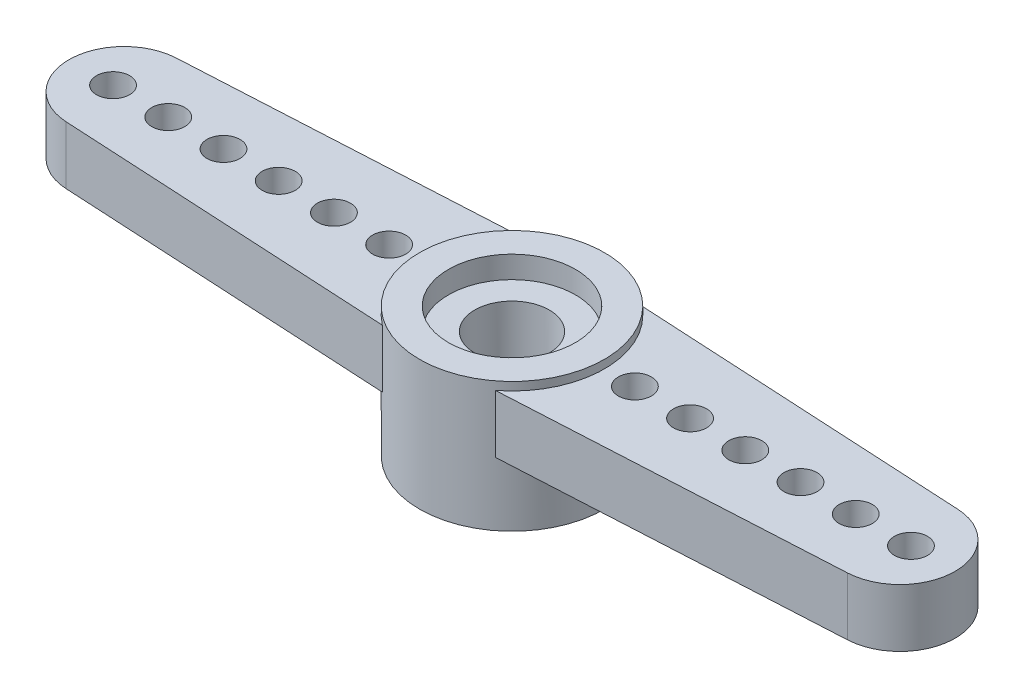
SolidWorks part; units mm, degrees
material "PVC Rígido"
ref_plane "Plano frontal" through (0, 0, 0) normal (0, 0, 1) x (1, 0, 0)
ref_plane "Plano superior" through (0, 0, 0) normal (0, 1, 0) x (1, 0, 0)
ref_plane "Plano direito" through (0, 0, 0) normal (1, 0, 0) x (0, 0, -1)
sketch "Esboço1" plane through (0, 0, 0) normal (0, 1, 0) x (1, 0, 0)
  line L0 (0, 0) -> (-14.05, 0) construction
  line L1 (-14.1577, 1.9971) -> (-2.0494, 2.65)
  line L2 (-2.0494, -2.65) -> (-14.1577, -1.9971)
  arc A0 (-2.0494, -2.65) -> (-2.0494, 2.65) centre (0, 0) ccw
  arc A1 (-14.1577, 1.9971) -> (-14.1577, -1.9971) centre (-14.05, 0) ccw
  point P5 (-16.05, 0)
  dimension "D1" = 6.7
  dimension "D2" = 4
  dimension "D3" = 16.05
  dimension "D4" = 5.3
extrude "Ressalto-extrusão1" add sketch "Esboço1" against normal blind 2.1
sketch "Esboço2" plane through (0, -2.1, 0) normal (0, -1, 0) x (1, 0, 0)
  arc A0 (-2.0494, -2.65) -> (-2.0494, 2.65) centre (0, 0) ccw construction
  circle A1 centre (0, 0) radius 3.35
extrude "Ressalto-extrusão2" add sketch "Esboço2" along normal offset from surface (2.3 mm away) 4.4 up to face at (-7.2268, 0, 0)
hole_wizard "Furo4" positions "Esboço9" profile "Esboço10" legacy end condition through all
sketch "Esboço9" plane through (0, 0, 0) normal (0, 1, 0) x (1, 0, 0)
  line L1 (-14.45, 0) -> (0, 0) construction
  arc A2 (-14.1577, 1.9971) -> (-14.1577, -1.9971) centre (-14.05, 0) ccw construction
  point P0 (-14.45, 0)
  point P19 (-16.05, 0)
  dimension "D1" = 1.6
sketch "Esboço10" plane through (-14.45, 0, 0) normal (1, 0, 0) x (0, 0, 1)
  line L0 (0, 0) -> (0, 4.4)
  line L1 (0, 4.4) -> (0.6, 4.4)
  line L2 (0.6, 4.4) -> (0.6, 0)
  line L3 (0.6, 0) -> (0, 0)
  line L4 (0, 110) -> (0, -10) construction
  dimension "Diameter" = 1.2
  dimension "Depth" = 4.4
pattern_linear "Padrão linear1" count 6 spacing 2 along (1, 0, 0) of "Furo4"
pattern_circular "PadrãoCircular2" count 2 over 360 about axis through (0, 0, 0) along (0, 1, 0) of "Ressalto-extrusão1", "Furo4", "Padrão linear1"
hole_wizard "Furo1" positions "Esboço3" profile "Esboço4" legacy
sketch "Esboço3" plane through (0, -4.4, 0) normal (0, -1, 0) x (-1, 0, 0)
  point P0 (0, 0)
sketch "Esboço4" plane through (0, -4.4, 0) normal (1, 0, 0) x (0, 0, -1)
  line L0 (0, 0) -> (0, 2)
  line L1 (0, 2) -> (2.475, 2)
  line L2 (2.475, 2) -> (2.475, 0)
  line L3 (2.475, 0) -> (0, 0)
  line L4 (0, 110) -> (0, -10) construction
  dimension "Diameter" = 4.95
  dimension "Depth" = 2
hole_wizard "Furo2" positions "Esboço5" profile "Esboço6" legacy
sketch "Esboço5" plane through (0, 0, 0) normal (0, 1, 0) x (1, 0, 0)
  point P0 (0, 0)
sketch "Esboço6" plane through (0, 0, 0) normal (1, 0, 0) x (0, 0, 1)
  line L0 (0, 0) -> (0, 0.5)
  line L1 (0, 0.5) -> (2.3, 0.5)
  line L2 (2.3, 0.5) -> (2.3, 0)
  line L3 (2.3, 0) -> (0, 0)
  line L4 (0, 110) -> (0, -10) construction
  dimension "Diameter" = 4.6
  dimension "Depth" = 0.5
hole_wizard "Furo3" positions "Esboço7" profile "Esboço8" legacy end condition through all
sketch "Esboço7" plane through (0, 0, 0) normal (0, 1, 0) x (1, 0, 0)
  point P0 (0, 0)
sketch "Esboço8" plane through (0, 0, 0) normal (1, 0, 0) x (0, 0, 1)
  line L0 (0, 0) -> (0, 4.4)
  line L1 (0, 4.4) -> (1.35, 4.4)
  line L2 (1.35, 4.4) -> (1.35, 0)
  line L3 (1.35, 0) -> (0, 0)
  line L4 (0, 110) -> (0, -10) construction
  dimension "Diameter" = 2.7
  dimension "Depth" = 4.4
sketch "Esboço11" plane through (0, -4.4, 0) normal (0, -1, 0) x (1, 0, 0)
  line L0 (-0.0981, 2.4731) -> (0, 2.375)
  line L1 (0, 2.375) -> (0.0981, 2.4731)
  line L2 (0, 0) -> (0, 2.475) construction
  circle A0 centre (0, 0) radius 2.375 construction
  circle A1 centre (0, 0) radius 2.475
  arc A2 (0.0981, 2.4731) -> (-0.0981, 2.4731) centre (0, 0) ccw
  dimension "D3" = 4.75
  dimension "D2" = 0.1
  dimension "D1" = 0
extrude "Ressalto-extrusão3" add sketch "Esboço11" against normal up to surface (2 mm away) up to face at (0, -2.4, 1.35)
pattern_circular "PadrãoCircular1" count 60 over 360 about axis through (0, 0, 0) along (0, 1, 0) of "Ressalto-extrusão3"
sketch "Sketch1" plane through (0, 0, 0) normal (0, 1, 0) x (1, 0, 0)
  circle A0 centre (0, 0) radius 3.35 construction
  circle A1 centre (0, 0) radius 3.35
  circle A2 centre (0, 0) radius 2.3 construction
  circle A3 centre (0, 0) radius 2.3
extrude "Boss-Extrude1" add sketch "Sketch1" along normal blind 0.3
